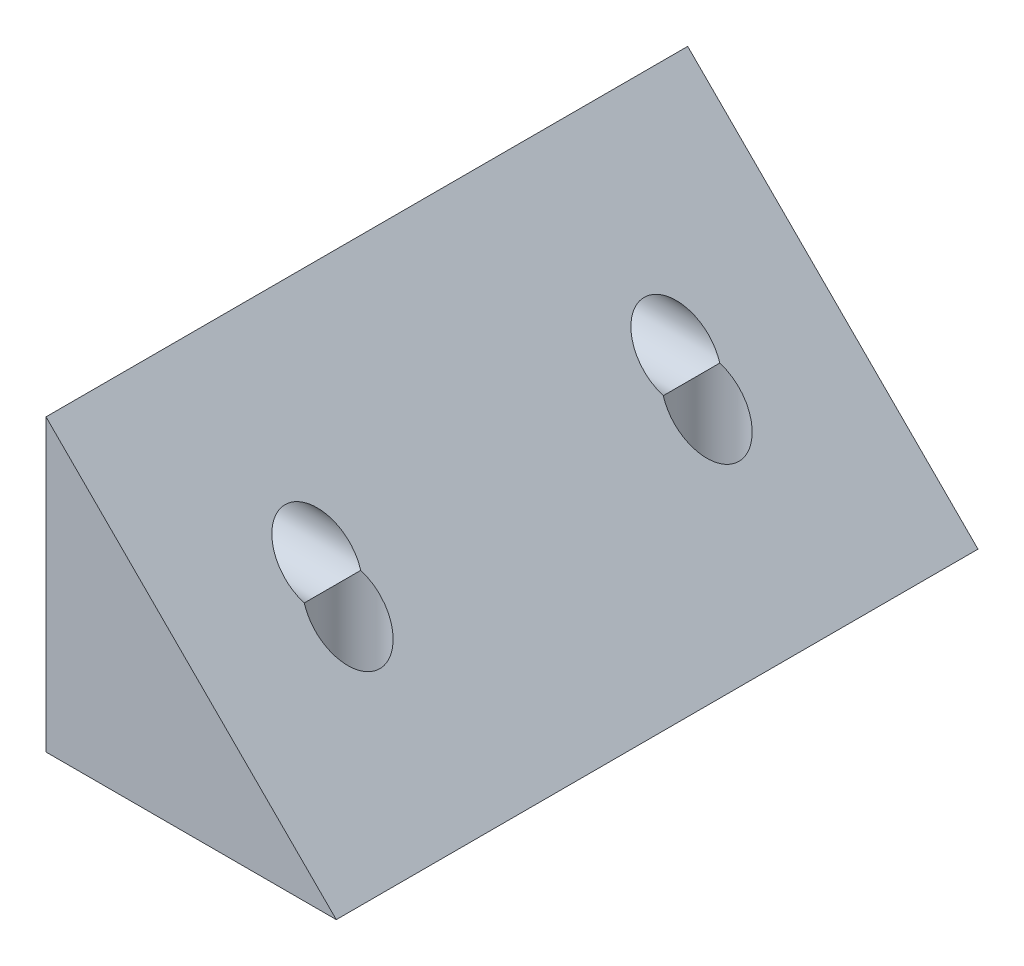
SolidWorks part; units mm, degrees
ref_plane "前视基准面" through (0, 0, 0) normal (0, 0, 1) x (1, 0, 0)
ref_plane "上视基准面" through (0, 0, 0) normal (0, 1, 0) x (1, 0, 0)
ref_plane "右视基准面" through (0, 0, 0) normal (1, 0, 0) x (0, 0, -1)
sketch "草图1" plane through (0, 0, 0) normal (0, 0, 1) x (1, 0, 0)
  line L1 (19, 0) -> (0, 0)
  line L2 (0, 0) -> (0, 19)
  line L3 (0, 19) -> (19, 0)
  dimension "D1" = 19
  dimension "D2" = 19
extrude "凸台-拉伸2" add sketch "草图1" along normal blind 42
sketch "草图4" plane through (0, 0, 0) normal (0, -1, 0) x (-1, 0, 0)
  line L0 (0, -21) -> (-19, -21) construction
  line L1 (0, -42) -> (0, 0) construction
  line L2 (-19, -42) -> (-19, 0) construction
  circle A0 centre (-10.5, -32.75) radius 2.1
  circle A1 centre (-10.5, -9.25) radius 2.1
  dimension "D3" = 4.2
  dimension "D1" = 8.5
  dimension "D2" = 11.75
extrude "切除-拉伸2" cut sketch "草图4" against normal blind 42
sketch "草图5" plane through (0, 0, 0) normal (-1, 0, 0) x (0, 0, 1)
  line L0 (21, 0) -> (21, 19) construction
  line L1 (42, 0) -> (0, 0) construction
  line L2 (42, 19) -> (0, 19) construction
  circle A0 centre (32.75, 10.5) radius 2.1
  circle A1 centre (9.25, 10.5) radius 2.1
  dimension "D1" = 4.2
  dimension "D2" = 8.5
  dimension "D3" = 11.75
extrude "切除-拉伸3" cut sketch "草图5" against normal blind 42
